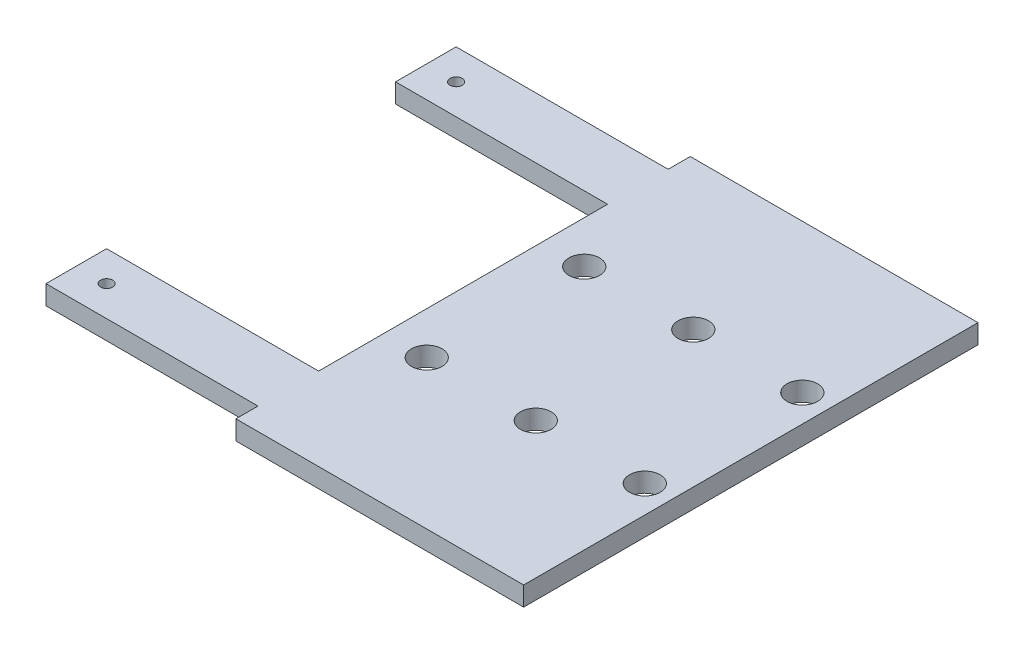
SolidWorks part; units mm, degrees
material "Plain Carbon Steel"
ref_plane "Front Plane" through (0, 0, 0) normal (0, 0, 1) x (1, 0, 0)
ref_plane "Top Plane" through (0, 0, 0) normal (0, 1, 0) x (1, 0, 0)
ref_plane "Right Plane" through (0, 0, 0) normal (1, 0, 0) x (0, 0, -1)
sketch "Sketch1" plane through (0, 0, 0) normal (0, 1, 0) x (1, 0, 0)
  line L0 (-120, -47.7) -> (-50, -47.7)
  line L1 (-36, 26) -> (36, 26) construction
  line L2 (-36, 26) -> (-36, -26) construction
  line L3 (-36, -26) -> (36, -26) construction
  line L4 (36, 26) -> (36, -26) construction
  line L5 (-36, 26) -> (36, -26) construction
  line L6 (-36, -26) -> (36, 26) construction
  line L7 (45, 75) -> (-50, 75)
  line L8 (45, 75) -> (45, -75)
  line L9 (45, -75) -> (-50, -75)
  line L10 (-120, 67.7) -> (-120, 47.7)
  line L11 (-50, -47.7) -> (-50, 47.7)
  line L12 (-50, 47.7) -> (-120, 47.7)
  line L13 (-120, -47.7) -> (-120, -67.7)
  line L14 (-120, 47.7) -> (-120, -47.7) construction
  line L15 (0, 0) -> (-120, 0) construction
  line L16 (-50, 75) -> (-50, 67.7)
  line L17 (-50, 67.7) -> (-120, 67.7)
  line L18 (-120, -67.7) -> (-50, -67.7)
  line L19 (-50, -67.7) -> (-50, -75)
  line L20 (-110, 57.7) -> (-110, -57.7) construction
  circle A0 centre (-36, 26) radius 5.05
  circle A1 centre (36, 26) radius 5.05
  circle A2 centre (36, -26) radius 5.05
  circle A3 centre (-36, -26) radius 5.05
  circle A4 centre (0, 26) radius 5.05
  circle A5 centre (0, -26) radius 5.05
  circle A6 centre (-110, 57.7) radius 2
  circle A7 centre (-110, -57.7) radius 2
  point P0 (0, 0)
  dimension "D3" = 10.1
  dimension "D12" = 4
  dimension "D1" = 52
  dimension "D2" = 72
  dimension "D4" = 45
  dimension "D5" = 75
  dimension "D6" = 75
  dimension "D7" = 95.4
  dimension "D8" = 20
  dimension "D9" = 50
  dimension "D10" = 120
  dimension "D11" = 10
  dimension "D13" = 10
  dimension "D14" = 10
extrude "Boss-Extrude1" add sketch "Sketch1" along normal blind 6.35
